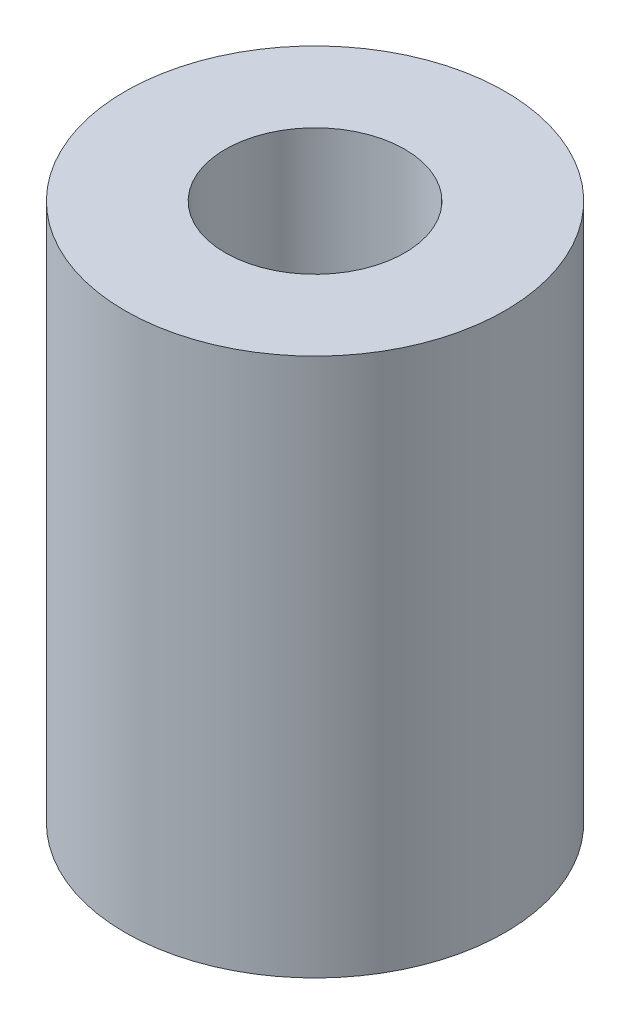
SolidWorks part; units mm, degrees
material "Alum 2011"
ref_plane "Front Plane" through (0, 0, 0) normal (0, 0, 1) x (1, 0, 0)
ref_plane "Top Plane" through (0, 0, 0) normal (0, 1, 0) x (1, 0, 0)
ref_plane "Right Plane" through (0, 0, 0) normal (1, 0, 0) x (0, 0, -1)
sketch "Sketch1" plane through (0, 0, 0) normal (0, 1, 0) x (1, 0, 0)
  circle A0 centre (0, 0) radius 3
  circle A1 centre (0, 0) radius 6.35
  dimension "D1" = 12.7
  dimension "D2" = 6
extrude "Boss-Extrude1" add sketch "Sketch1" along normal blind 18
